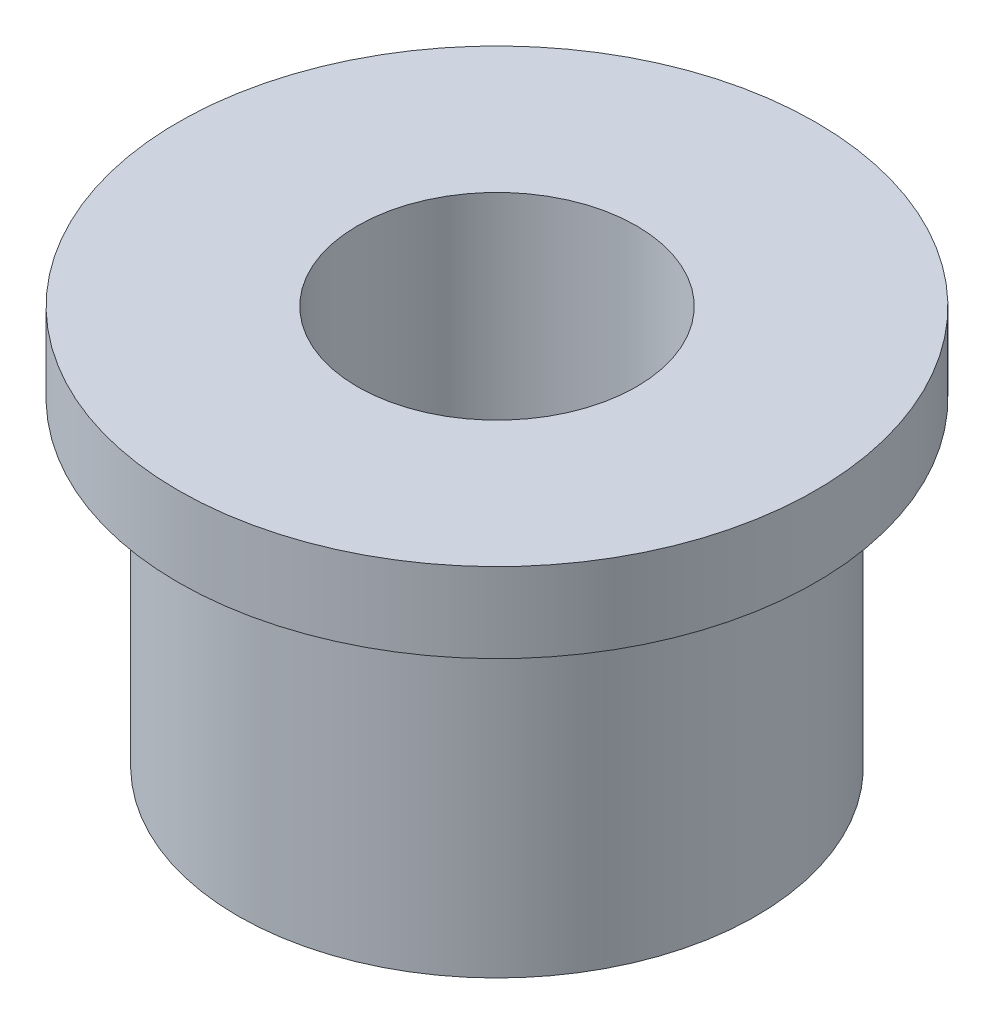
SolidWorks part; units mm, degrees
ref_plane "Front Plane" through (0, 0, 0) normal (0, 0, 1) x (1, 0, 0)
ref_plane "Top Plane" through (0, 0, 0) normal (0, 1, 0) x (1, 0, 0)
ref_plane "Right Plane" through (0, 0, 0) normal (1, 0, 0) x (0, 0, -1)
sketch "Sketch1" plane through (0, 0, 0) normal (0, 0, 1) x (1, 0, 0)
  line L0 (6.5, 0) -> (6.5, 8)
  line L1 (6.5, 8) -> (8, 8)
  line L2 (8, 8) -> (8, 10)
  line L3 (8, 10) -> (3.5, 10)
  line L4 (3.5, 10) -> (3.5, 2)
  line L5 (3.5, 2) -> (6.5, 0)
  line L6 (0, 8.948) -> (0, 0) construction
  dimension "D1" = 3.5
  dimension "D2" = 8
  dimension "D3" = 2
  dimension "D4" = 2
  dimension "D5" = 10
  dimension "D6" = 6.5
revolve "Revolve1" add sketch "Sketch1" angle 360 about L6
